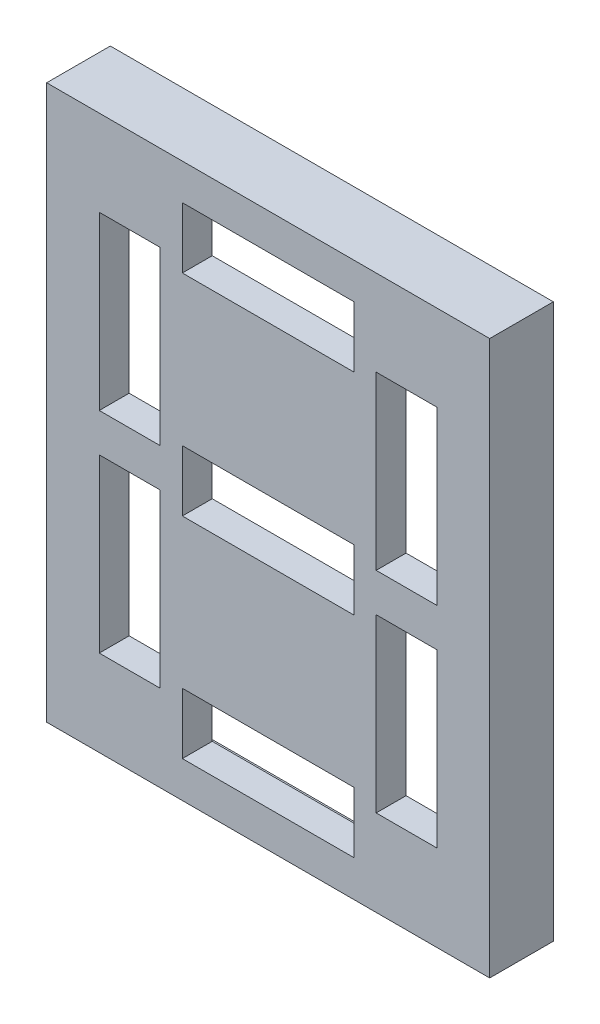
SolidWorks part; units mm, degrees
ref_plane "Front Plane" through (0, 0, 0) normal (0, 0, 1) x (1, 0, 0)
ref_plane "Top Plane" through (0, 0, 0) normal (0, 1, 0) x (1, 0, 0)
ref_plane "Right Plane" through (0, 0, 0) normal (1, 0, 0) x (0, 0, -1)
sketch "Sketch1" plane through (0, 0, 0) normal (0, 0, 1) x (1, 0, 0)
  line L4 (40, -50) -> (-40, -50)
  line L5 (40, 50) -> (40, -50)
  line L6 (-40, 50) -> (40, 50)
  line L7 (-40, -50) -> (-40, 50)
  line L8 (-39.25, -49.25) -> (-39.25, 49.25)
  line L9 (-39.25, 49.25) -> (39.25, 49.25)
  line L10 (39.25, 49.25) -> (39.25, -49.25)
  line L11 (39.25, -49.25) -> (-39.25, -49.25)
  line L12 (-16.5, 44.5) -> (-19.05, 38.013)
  line L13 (-16.5, 44.5) -> (16.5, 44.5)
  line L14 (16.5, 44.5) -> (19.05, 38.013)
  line L15 (-1000, 38.013) -> (49000, 38.013) construction
  line L16 (16.5, 31.526) -> (19.05, 38.013)
  line L17 (-16.5, 31.526) -> (16.5, 31.526)
  line L18 (-16.5, 31.526) -> (-19.05, 38.013)
  line L19 (-1000, 0.0306) -> (-26.3532, 0.0306) construction
  line L26 (-15.5, 43.5) -> (15.5, 43.5)
  line L27 (15.5, 43.5) -> (15.5, 32.5)
  line L28 (15.5, 32.5) -> (-15.5, 32.5)
  line L29 (-15.5, 32.5) -> (-15.5, 43.5)
  line L30 (15.5, -32.4388) -> (-15.5, -32.4388)
  line L31 (15.5, -43.4388) -> (15.5, -32.4388)
  line L32 (-15.5, -43.4388) -> (15.5, -43.4388)
  line L33 (-15.5, -32.4388) -> (-15.5, -43.4388)
  line L34 (-16.5, -31.4648) -> (16.5, -31.4648)
  line L35 (-16.5, -31.4648) -> (-19.05, -37.9518)
  line L36 (-16.5, -44.4388) -> (-19.05, -37.9518)
  line L37 (-16.5, -44.4388) -> (16.5, -44.4388)
  line L38 (16.5, -44.4388) -> (19.05, -37.9518)
  line L39 (16.5, -31.4648) -> (19.05, -37.9518)
  line L40 (-19.05, 0.0306) -> (-16.5, 6.5)
  line L41 (-16.5, 6.5) -> (16.5, 6.5)
  line L42 (16.5, 6.5) -> (19.05, 0.0306)
  line L43 (-15.5, 5.5) -> (-15.5, -5.5)
  line L44 (-15.5, -5.5) -> (15.5, -5.5)
  line L45 (15.5, -5.5) -> (15.5, 5.5)
  line L46 (15.5, 5.5) -> (-15.5, 5.5)
  line L47 (16.5, -6.4388) -> (19.05, 0.0306)
  line L48 (-16.5, -6.4388) -> (16.5, -6.4388)
  line L49 (-19.05, 0.0306) -> (-16.5, -6.4388)
  line L50 (-31.5, 35.5) -> (-25.0832, 38.05)
  line L51 (-25.0832, 38.05) -> (-18.5, 35.5)
  line L52 (-18.5, 35.5) -> (-18.5, 2.5)
  line L53 (-18.5, 2.5) -> (-23.8468, 0.429)
  line L55 (-31.5, 2.5) -> (-31.5, 35.5)
  line L56 (0, -999.9694) -> (0, 49000.0306) construction
  line L57 (-30.5, 34.5) -> (-19.5, 34.5)
  line L58 (-19.5, 34.5) -> (-19.5, 3.5)
  line L59 (-19.5, 3.5) -> (-30.5, 3.5)
  line L60 (-30.5, 3.5) -> (-30.5, 34.5)
  line L62 (18.5, 2.5) -> (23.8468, 0.429)
  line L63 (18.5, 35.5) -> (18.5, 2.5)
  line L64 (25.0832, 38.05) -> (18.5, 35.5)
  line L65 (31.5, 35.5) -> (25.0832, 38.05)
  line L66 (31.5, 2.5) -> (31.5, 35.5)
  line L67 (19.5, 3.5) -> (30.5, 3.5)
  line L68 (19.5, 34.5) -> (19.5, 3.5)
  line L69 (30.5, 34.5) -> (19.5, 34.5)
  line L70 (30.5, 3.5) -> (30.5, 34.5)
  line L71 (19.5, -34.4388) -> (19.5, -3.4388)
  line L72 (30.5, -34.4388) -> (19.5, -34.4388)
  line L73 (30.5, -3.4388) -> (30.5, -34.4388)
  line L74 (19.5, -3.4388) -> (30.5, -3.4388)
  line L75 (18.5, -2.4388) -> (23.8468, -0.3677)
  line L76 (18.5, -35.4388) -> (18.5, -2.4388)
  line L77 (25.0832, -37.9888) -> (18.5, -35.4388)
  line L78 (31.5, -35.4388) -> (25.0832, -37.9888)
  line L79 (31.5, -2.4388) -> (31.5, -35.4388)
  line L81 (-19.5, -3.4388) -> (-30.5, -3.4388)
  line L82 (-19.5, -34.4388) -> (-19.5, -3.4388)
  line L83 (-30.5, -34.4388) -> (-19.5, -34.4388)
  line L84 (-30.5, -3.4388) -> (-30.5, -34.4388)
  line L86 (-18.5, -2.4388) -> (-23.8468, -0.3677)
  line L87 (-18.5, -35.4388) -> (-18.5, -2.4388)
  line L88 (-25.0832, -37.9888) -> (-18.5, -35.4388)
  line L89 (-31.5, -35.4388) -> (-25.0832, -37.9888)
  line L90 (-31.5, -2.4388) -> (-31.5, -35.4388)
  line L91 (-25.0832, 0.1112) -> (-25.0832, 0.0306) construction
  line L92 (23.8468, -0.3677) -> (23.6168, 0.0306)
  line L93 (-23.6168, 0.0306) -> (-23.8468, 0.429)
  line L95 (-26.3139, 0.4391) -> (-26.5497, 0.0306)
  line L96 (-26.5497, 0.0306) -> (-26.3139, -0.3778)
  line L98 (-23.8468, -0.3677) -> (-23.6168, 0.0306)
  line L100 (26.5497, 0.0306) -> (26.3139, -0.3778)
  line L101 (26.3139, 0.4391) -> (26.5497, 0.0306)
  line L103 (23.6168, 0.0306) -> (23.8468, 0.429)
  line L104 (-26.3139, -0.3778) -> (-31.5, -2.4388)
  line L105 (-25.0832, -1.2394) -> (-24.35, -1.2394) [skipped]
  line L107 (-23.8132, 0.0306) -> (49000, 0.0306) construction
  line L110 (-26.3139, 0.4391) -> (-31.5, 2.5)
  line L111 (-24.35, 1.3006) -> (-25.0832, 1.3006) [skipped]
  line L113 (26.3139, -0.3778) -> (31.5, -2.4388)
  line L114 (26.3139, 0.4391) -> (31.5, 2.5)
  arc A0 (-23.8132, 0.0306) -> (-23.8739, 0.4184) centre (-25.0832, 0.0306) ccw construction
  arc A1 (-26.2891, 0.4292) -> (-26.2891, -0.3679) centre (-25.0832, 0.0306) ccw construction
  point P0 (-25.0832, -19)
  point P2 (24.5348, -19.0864)
  point P6 (0, 0)
  point P8 (25.0842, 19)
  point P10 (-25.0832, 19)
  point P12 (0, 38.013)
  dimension "D6" = 2.54
  dimension "D2" = 19.05
  dimension "D3" = 38.1
  dimension "D4" = 19.05
  dimension "D1" = 0.75
extrude "Boss-Extrude1" add sketch "Sketch1" along normal blind 3.81 contours L110 L95 L96 L104 L90 L89 L88 L87 L86 L98 L93 L53 L52 L51 L50 L55 L84 L81 L82 L83 L59 L60 L57 L58 | L40 L49 L48 L47 L42 L41 L46 L45 L44 L43 | L101 L114 L66 L65 L64 L63 L62 L103 L92 L75 L76 L77 L78 L79 L113 L100 L70 L67 L68 L69 L71 L74 L73 L72 | L18 L17 L16 L14 L13 L12 L28 L29 L26 L27 | L39 L34 L35 L36 L37 L38 L33 L30 L31 L32 | L7 L4 L5 L6 L10 L11 L8 L9
sketch "Sketch3" plane through (0, 0, 3.81) normal (0, 0, 1) x (1, 0, 0)
  line L0 (15.5, -43.4388) -> (15.5, -32.4388) construction
  line L1 (-15.5, -43.4388) -> (15.5, -43.4388) construction
  line L2 (-15.5, -32.4388) -> (-15.5, -43.4388) construction
  line L3 (15.5, -32.4388) -> (-15.5, -32.4388) construction
  line L4 (15.5, -5.5) -> (15.5, 5.5) construction
  line L5 (-15.5, -5.5) -> (15.5, -5.5) construction
  line L6 (-15.5, 5.5) -> (-15.5, -5.5) construction
  line L7 (15.5, 5.5) -> (-15.5, 5.5) construction
  line L8 (-30.5, -34.4388) -> (-19.5, -34.4388) construction
  line L9 (-19.5, -34.4388) -> (-19.5, -3.4388) construction
  line L10 (-30.5, -3.4388) -> (-30.5, -34.4388) construction
  line L11 (-19.5, -3.4388) -> (-30.5, -3.4388) construction
  line L12 (-19.5, 3.5) -> (-30.5, 3.5) construction
  line L13 (-19.5, 34.5) -> (-19.5, 3.5) construction
  line L14 (-30.5, 3.5) -> (-30.5, 34.5) construction
  line L15 (-30.5, 34.5) -> (-19.5, 34.5) construction
  line L16 (-15.5, 32.5) -> (-15.5, 43.5) construction
  line L17 (15.5, 32.5) -> (-15.5, 32.5) construction
  line L18 (15.5, 43.5) -> (15.5, 32.5) construction
  line L19 (-15.5, 43.5) -> (15.5, 43.5) construction
  line L20 (19.5, 3.5) -> (30.5, 3.5) construction
  line L21 (30.5, 3.5) -> (30.5, 34.5) construction
  line L22 (30.5, 34.5) -> (19.5, 34.5) construction
  line L23 (19.5, 34.5) -> (19.5, 3.5) construction
  line L24 (30.5, -34.4388) -> (19.5, -34.4388) construction
  line L25 (30.5, -3.4388) -> (30.5, -34.4388) construction
  line L26 (19.5, -34.4388) -> (19.5, -3.4388) construction
  line L27 (19.5, -3.4388) -> (30.5, -3.4388) construction
  line L28 (40, -50) -> (-40, -50) construction
  line L29 (40, 50) -> (40, -50) construction
  line L30 (-40, 50) -> (40, 50) construction
  line L31 (-40, -50) -> (-40, 50) construction
  line L32 (15.5, -43.4388) -> (15.5, -32.4388)
  line L33 (-15.5, -43.4388) -> (15.5, -43.4388)
  line L34 (-15.5, -32.4388) -> (-15.5, -43.4388)
  line L35 (15.5, -32.4388) -> (-15.5, -32.4388)
  line L36 (15.5, -5.5) -> (15.5, 5.5)
  line L37 (-15.5, -5.5) -> (15.5, -5.5)
  line L38 (-15.5, 5.5) -> (-15.5, -5.5)
  line L39 (15.5, 5.5) -> (-15.5, 5.5)
  line L40 (-30.5, -34.4388) -> (-19.5, -34.4388)
  line L41 (-19.5, -34.4388) -> (-19.5, -3.4388)
  line L42 (-30.5, -3.4388) -> (-30.5, -34.4388)
  line L43 (-19.5, -3.4388) -> (-30.5, -3.4388)
  line L44 (-19.5, 3.5) -> (-30.5, 3.5)
  line L45 (-19.5, 34.5) -> (-19.5, 3.5)
  line L46 (-30.5, 3.5) -> (-30.5, 34.5)
  line L47 (-30.5, 34.5) -> (-19.5, 34.5)
  line L48 (-15.5, 32.5) -> (-15.5, 43.5)
  line L49 (15.5, 32.5) -> (-15.5, 32.5)
  line L50 (15.5, 43.5) -> (15.5, 32.5)
  line L51 (-15.5, 43.5) -> (15.5, 43.5)
  line L52 (19.5, 3.5) -> (30.5, 3.5)
  line L53 (30.5, 3.5) -> (30.5, 34.5)
  line L54 (30.5, 34.5) -> (19.5, 34.5)
  line L55 (19.5, 34.5) -> (19.5, 3.5)
  line L56 (30.5, -34.4388) -> (19.5, -34.4388)
  line L57 (30.5, -3.4388) -> (30.5, -34.4388)
  line L58 (19.5, -34.4388) -> (19.5, -3.4388)
  line L59 (19.5, -3.4388) -> (30.5, -3.4388)
  line L60 (40, -50) -> (-40, -50)
  line L61 (40, 50) -> (40, -50)
  line L62 (-40, 50) -> (40, 50)
  line L63 (-40, -50) -> (-40, 50)
extrude "Boss-Extrude2" add sketch "Sketch3" along normal blind 1.5875
fillet "Fillet1" radius 0.05 4 edges at (39.25, -49.25, 1.905) (-39.25, -49.25, 1.905) (-39.25, 49.25, 1.905) (39.25, 49.25, 1.905)
sketch "Sketch9" plane through (0, 0, 0) normal (0, 0, -1) x (-1, 0, 0)
  line L0 (39.2, 49.25) -> (-39.2, 49.25) construction
  line L1 (-39.25, 49.2) -> (-39.25, -49.2) construction
  line L2 (39.25, -49.2) -> (39.25, 49.2) construction
  line L3 (-39.2, -49.25) -> (39.2, -49.25) construction
  line L4 (40, -50) -> (40, 50)
  line L5 (40, 50) -> (-40, 50)
  line L6 (-40, 50) -> (-40, -50)
  line L7 (-40, -50) -> (40, -50)
  line L8 (40, -50) -> (40, 50)
  line L9 (40, 50) -> (-40, 50)
  line L10 (-40, 50) -> (-40, -50)
  line L11 (-40, -50) -> (40, -50)
  line L12 (39.2, 49.25) -> (-39.2, 49.25)
  line L13 (-39.25, 49.2) -> (-39.25, -49.2)
  line L14 (39.25, -49.2) -> (39.25, 49.2)
  line L15 (-39.2, -49.25) -> (39.2, -49.25)
  arc A0 (39.2, -49.25) -> (39.25, -49.2) centre (39.2, -49.2) ccw construction
  arc A1 (-39.25, -49.2) -> (-39.2, -49.25) centre (-39.2, -49.2) ccw construction
  arc A2 (39.25, 49.2) -> (39.2, 49.25) centre (39.2, 49.2) ccw construction
  arc A3 (-39.2, 49.25) -> (-39.25, 49.2) centre (-39.2, 49.2) ccw construction
  arc A4 (39.2, -49.25) -> (39.25, -49.2) centre (39.2, -49.2) ccw
  arc A5 (-39.25, -49.2) -> (-39.2, -49.25) centre (-39.2, -49.2) ccw
  arc A6 (39.25, 49.2) -> (39.2, 49.25) centre (39.2, 49.2) ccw
  arc A7 (-39.2, 49.25) -> (-39.25, 49.2) centre (-39.2, 49.2) ccw
  dimension "D1" = 0
extrude "Boss-Extrude6" add sketch "Sketch9" along normal blind 6.096
